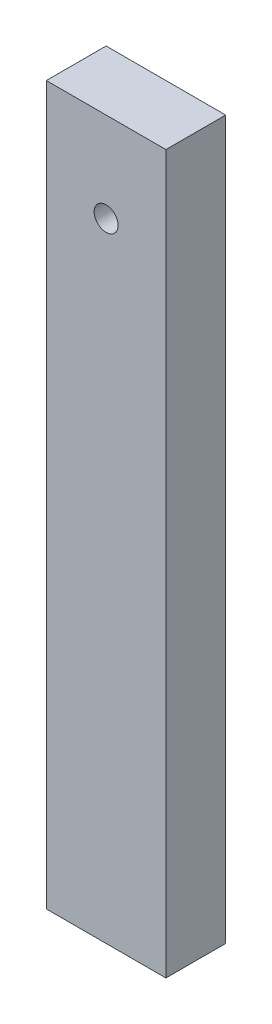
SolidWorks part; units mm, degrees
ref_plane "Front Plane" through (0, 0, 0) normal (0, 0, 1) x (1, 0, 0)
ref_plane "Top Plane" through (0, 0, 0) normal (0, 1, 0) x (1, 0, 0)
ref_plane "Right Plane" through (0, 0, 0) normal (1, 0, 0) x (0, 0, -1)
sketch "Sketch1" plane through (0, 0, 0) normal (0, 1, 0) x (1, 0, 0)
  line L1 (0, 0) -> (25.4, 0)
  line L2 (0, 0) -> (0, 12.7)
  line L3 (0, 12.7) -> (25.4, 12.7)
  line L4 (25.4, 0) -> (25.4, 12.7)
  dimension "D1" = 25.4
  dimension "D2" = 12.7
extrude "Boss-Extrude2" add sketch "Sketch1" along normal blind 152.4 contours L3 L4 L1 L2
sketch "Sketch2" plane through (0, 0, 0) normal (0, 0, 1) x (1, 0, 0)
  line L0 (0, 152.4) -> (25.4, 152.4) construction
  line L1 (25.4, 152.4) -> (25.4, 0) construction
  circle A0 centre (12.7, 133.35) radius 2.54
  point P4 (0, 0)
  dimension "D1" = 5.08
  dimension "D2" = 19.05
  dimension "D3" = 12.7
extrude "Cut-Extrude2" cut sketch "Sketch2" against normal blind 22.86 contours A0
